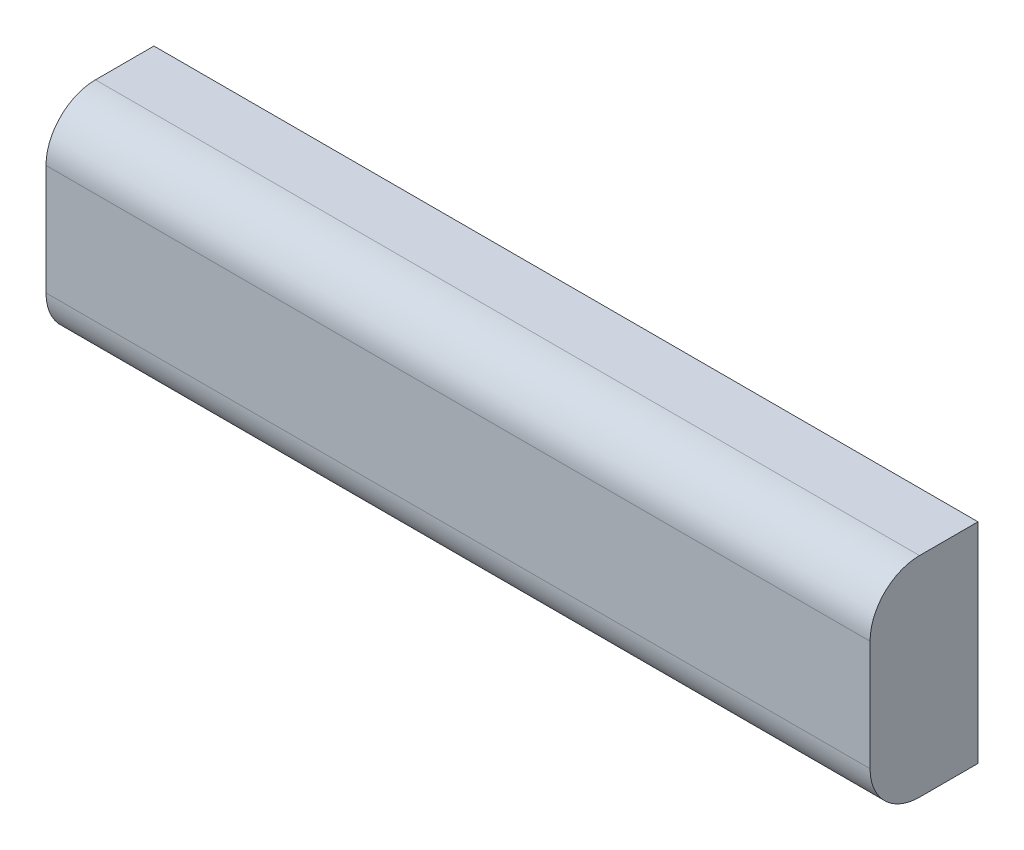
SolidWorks part; units mm, degrees
ref_plane "Front Plane" through (0, 0, 0) normal (0, 0, 1) x (1, 0, 0)
ref_plane "Top Plane" through (0, 0, 0) normal (0, 1, 0) x (1, 0, 0)
ref_plane "Right Plane" through (0, 0, 0) normal (1, 0, 0) x (0, 0, -1)
sketch "Sketch1" plane through (0, 0, 0) normal (0, 0, 1) x (1, 0, 0)
  line L1 (25, -6.35) -> (-25, -6.35)
  line L2 (25, -6.35) -> (25, 6.35)
  line L3 (25, 6.35) -> (-25, 6.35)
  line L4 (-25, -6.35) -> (-25, 6.35)
  line L5 (25, -6.35) -> (-25, 6.35) construction
  line L6 (25, 6.35) -> (-25, -6.35) construction
  point P0 (0, 0)
  dimension "D1" = 12.7
  dimension "D2" = 50
extrude "Boss-Extrude1" add sketch "Sketch1" along normal blind 6.55
sketch "Sketch2" plane through (0, 0, 0) normal (0, 0, -1) x (-1, 0, 0)
  line L1 (24, -3.16) -> (-24, -3.16)
  line L2 (24, -3.16) -> (24, 3.16)
  line L3 (24, 3.16) -> (-24, 3.16)
  line L4 (-24, -3.16) -> (-24, 3.16)
  line L5 (24, -3.16) -> (-24, 3.16) construction
  line L6 (24, 3.16) -> (-24, -3.16) construction
  point P0 (0, 0)
  dimension "D1" = 48
  dimension "D2" = 6.32
extrude "Cut-Extrude2" cut sketch "Sketch2" against normal blind 6.35
fillet "Fillet1" radius 3 2 edges at (0, -6.35, 6.55) (0, 6.35, 6.55)
